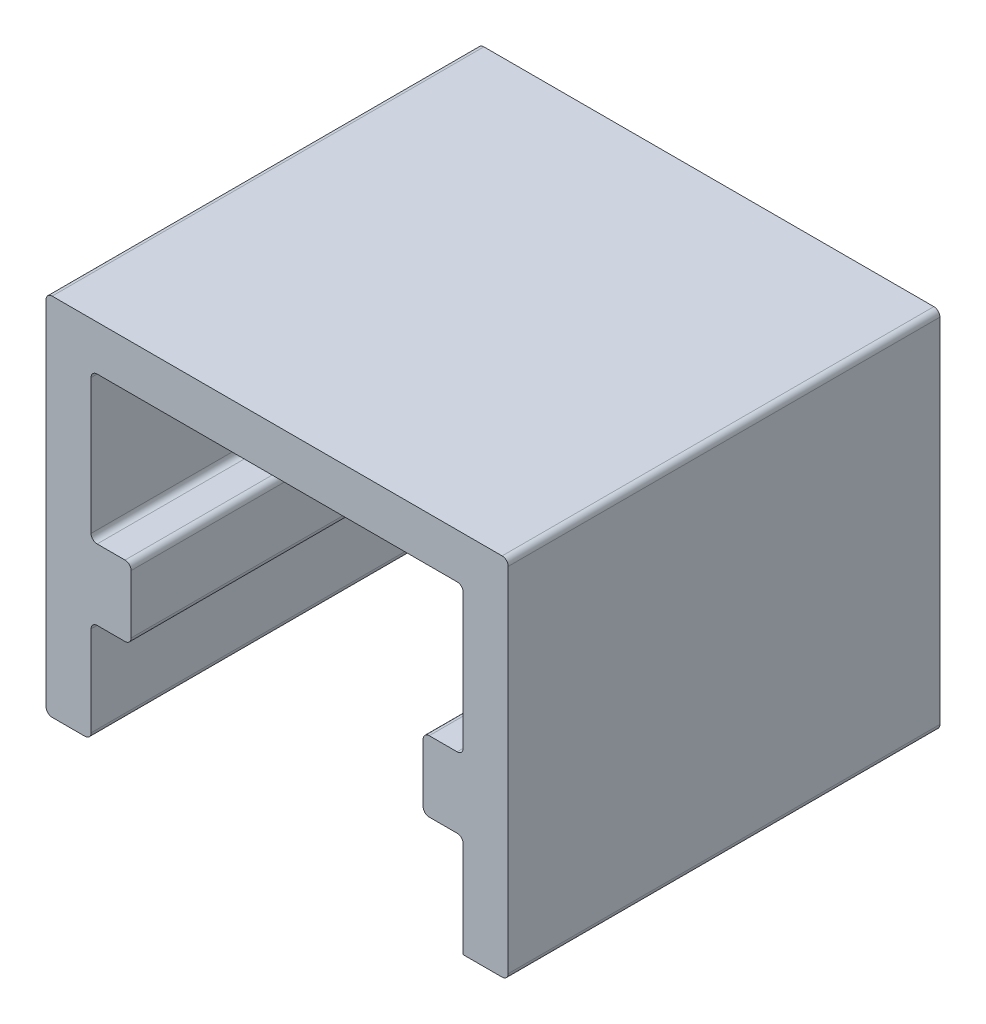
SolidWorks part; units mm, degrees
ref_plane "Front Plane" through (0, 0, 0) normal (0, 0, 1) x (1, 0, 0)
ref_plane "Top Plane" through (0, 0, 0) normal (0, 1, 0) x (1, 0, 0)
ref_plane "Right Plane" through (0, 0, 0) normal (1, 0, 0) x (0, 0, -1)
sketch "Sketch1" plane through (0, 0, 0) normal (0, 0, 1) x (1, 0, 0)
  line L1 (-24.13, -19.05) -> (24.13, -19.05)
  line L2 (-24.13, -19.05) -> (-24.13, 19.05)
  line L3 (-24.13, 19.05) -> (24.13, 19.05)
  line L4 (24.13, -19.05) -> (24.13, 19.05)
  line L5 (-24.13, -19.05) -> (24.13, 19.05) construction
  line L6 (-24.13, 19.05) -> (24.13, -19.05) construction
  point P0 (0, 0)
  dimension "D1" = 48.26
  dimension "D2" = 38.1
extrude "Boss-Extrude1" add sketch "Sketch1" along normal blind 10.16
sketch "Sketch5" plane through (0, 0, 10.16) normal (0, 0, 1) x (1, 0, 0)
  line L0 (-24.13, -19.05) -> (-24.13, 19.05)
  line L1 (-24.13, 19.05) -> (24.13, 19.05)
  line L2 (24.13, 19.05) -> (24.13, -19.05)
  line L3 (24.13, -19.05) -> (19.431, -19.05)
  line L4 (-24.13, -19.05) -> (24.13, -19.05) construction
  line L5 (19.431, -19.05) -> (19.431, 14.351)
  line L6 (19.431, 14.351) -> (-19.431, 14.351)
  line L7 (-19.431, 14.351) -> (-19.431, -19.05)
  line L8 (-19.431, -19.05) -> (-24.13, -19.05)
  dimension "D1" = 38.862
  dimension "D2" = 19.431
  dimension "D3" = 4.699
  dimension "D4" = 4.699
extrude "Boss-Extrude3" add sketch "Sketch5" along normal blind 34.925 contours L7 L8 L0 L1 L2 L3 L5 L6
sketch "Sketch6" plane through (0, 0, 45.085) normal (0, 0, 1) x (1, 0, 0)
  circle A0 centre (19.431, 14.351) radius 0.9525
  dimension "D1" = 1.905
extrude "Cut-Extrude1" [suppressed] cut sketch "Sketch6" against normal up to surface (34.925 mm away)
mirror "Mirror1" [suppressed] about plane through (0, 0, 0) normal (1, 0, 0)
hole_wizard "CBORE for 5/16 Socket Head Cap Screw1" positions "Sketch3" profile "Sketch4" counterbore size "5/16" standard "ANSI Inch" end condition through all
sketch "Sketch3" plane through (0, 0, 0) normal (0, 0, -1) x (-1, 0, 0)
  line L0 (-19.431, 14.351) -> (19.431, 14.351) construction
  point P0 (0, -4.699)
  dimension "D1" = 19.05
sketch "Sketch4" plane through (0, -4.699, 0) normal (1, 0, 0) x (0, 1, 0)
  line L0 (0, 0) -> (0, 45.085)
  line L1 (0, 45.085) -> (4.1021, 45.085)
  line L3 (4.1021, 45.085) -> (4.1021, 5.3975)
  line L4 (4.1021, 5.3975) -> (6.7475, 5.3975)
  line L5 (6.7475, 5.3975) -> (6.7475, 0)
  line L7 (6.7475, 0) -> (0, 0)
  line L11 (0, -6.35) -> (0, 107.95) construction
  dimension "Thru Hole Dia." = 8.2042
  dimension "Thru Hole Depth" = 45.085
  dimension "C'Bore Dia." = 13.495
  dimension "C'Bore Depth" = 5.3975
sketch "Sketch7" plane through (0, 0, 10.16) normal (0, 0, 1) x (1, 0, 0)
  circle A0 centre (0, -4.699) radius 5.715
  dimension "D1" = 11.43
extrude "Cut-Extrude2" cut sketch "Sketch7" against normal blind 1.905
sketch "Sketch8" plane through (0, 0, 10.16) normal (0, 0, 1) x (1, 0, 0)
  line L0 (-19.431, 14.351) -> (-19.431, -19.05) construction
  line L1 (-15.2486, -8.382) -> (-19.431, -8.382)
  line L2 (-15.2486, -8.382) -> (-15.2486, -1.016)
  line L3 (-15.2486, -1.016) -> (-19.431, -1.016)
  line L4 (-19.431, -8.382) -> (-19.431, -1.016)
  dimension "D1" = 7.366
  dimension "D2" = 3.683
extrude "Boss-Extrude4" add sketch "Sketch8" along normal up to surface (34.925 mm away) up to face at (0, -1.1748, 45.085)
fillet "Fillet2" radius 0.635 2 edges at (19.431, 14.351, 27.6225) (-19.431, 14.351, 27.6225)
fillet "Fillet3" radius 0.635 5 edges at (24.13, 19.05, 22.5425) (-24.13, 19.05, 22.5425) (-19.431, -19.05, 27.6225) (-24.13, -19.05, 22.5425) (24.13, -19.05, 22.5425)
mirror "Mirror2" about plane through (0, 0, 0) normal (1, 0, 0) of "Boss-Extrude4"
fillet "Fillet1" radius 0.635 8 edges at (-19.431, -8.382, 27.6225) (-15.2486, -8.382, 27.6225) (-19.431, -1.016, 27.6225) (-15.2486, -1.016, 27.6225) (15.2486, -8.382, 27.6225) (19.431, -8.382, 27.6225) (15.2486, -1.016, 27.6225) (19.431, -1.016, 27.6225)
equation "\"D2@Sketch5\"=\"D1@Sketch5\"/2"
equation "\"D4@Sketch5\"=\"D3@Sketch5\""
equation "\"D2@Sketch8\"=\"D1@Sketch8\"/2"
